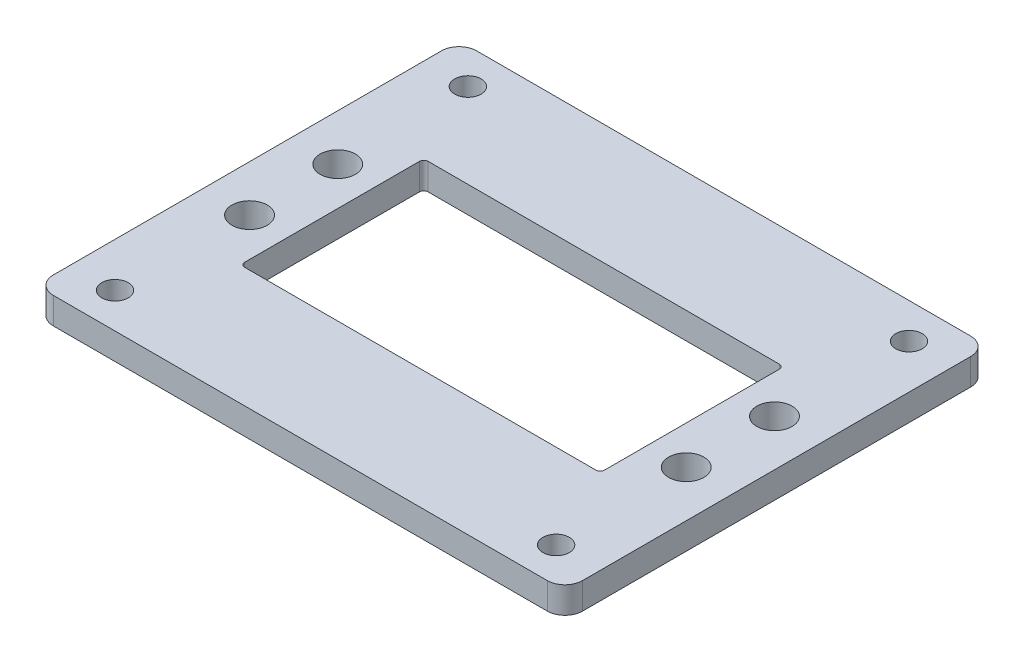
SolidWorks part; units mm, degrees
material "Thornel Mat VMA"
ref_plane "前视基准面" through (0, 0, 0) normal (0, 0, 1) x (1, 0, 0)
ref_plane "上视基准面" through (0, 0, 0) normal (0, 1, 0) x (1, 0, 0)
ref_plane "右视基准面" through (0, 0, 0) normal (1, 0, 0) x (0, 0, -1)
other "Configuration Table"
sketch "草图1" plane through (0, 0, 0) normal (0, 1, 0) x (1, 0, 0)
  line L0 (0, 0) -> (0, 29.6725) construction
  line L1 (-30, -24) -> (30, -24)
  line L2 (-30, -24) -> (-30, 24)
  line L3 (-30, 24) -> (30, 24)
  line L4 (30, -24) -> (30, 24)
  line L5 (-30, -24) -> (30, 24) construction
  line L6 (-30, 24) -> (30, -24) construction
  line L11 (-17.6814, -14.1451) -> (17.1506, 13.7205) construction
  line L13 (-20.4, -10.4) -> (20.4, -10.4)
  line L14 (-20.4, -10.4) -> (-20.4, 10.4)
  line L15 (-20.4, 10.4) -> (20.4, 10.4)
  line L16 (20.4, -10.4) -> (20.4, 10.4)
  line L17 (-20.4, -10.4) -> (20.4, 10.4) construction
  line L18 (-20.4, 10.4) -> (20.4, -10.4) construction
  line L19 (0, 0) -> (43.0948, 0) construction
  circle A0 centre (24.75, 5) radius 2
  circle A1 centre (24.75, -5) radius 2
  circle A2 centre (-24.75, -5) radius 2
  circle A3 centre (-24.75, 5) radius 2
  circle A4 centre (-25, 20) radius 1.5
  circle A5 centre (25, 20) radius 1.5
  circle A6 centre (25, -20) radius 1.5
  circle A7 centre (-25, -20) radius 1.5
  point P0 (0, 0)
  point P6 (0, 0)
  point P13 (0, 0)
  dimension "D5" = 4
  dimension "D8" = 3
  dimension "D7" = 49.5
  dimension "D1" = 60
  dimension "D2" = 48
  dimension "D3" = 40.8
  dimension "D4" = 20.8
  dimension "D6" = 5
  dimension "D9" = 25
  dimension "D10" = 20
extrude "凸台-拉伸1" add sketch "草图1" along normal blind 3
fillet "圆角1" radius 0.5 4 edges at (20.4, 1.5, 10.4) (-20.4, 1.5, 10.4) (20.4, 1.5, -10.4) (-20.4, 1.5, -10.4)
fillet "圆角2" radius 2 4 edges at (30, 1.5, -24) (30, 1.5, 24) (-30, 1.5, -24) (-30, 1.5, 24)
